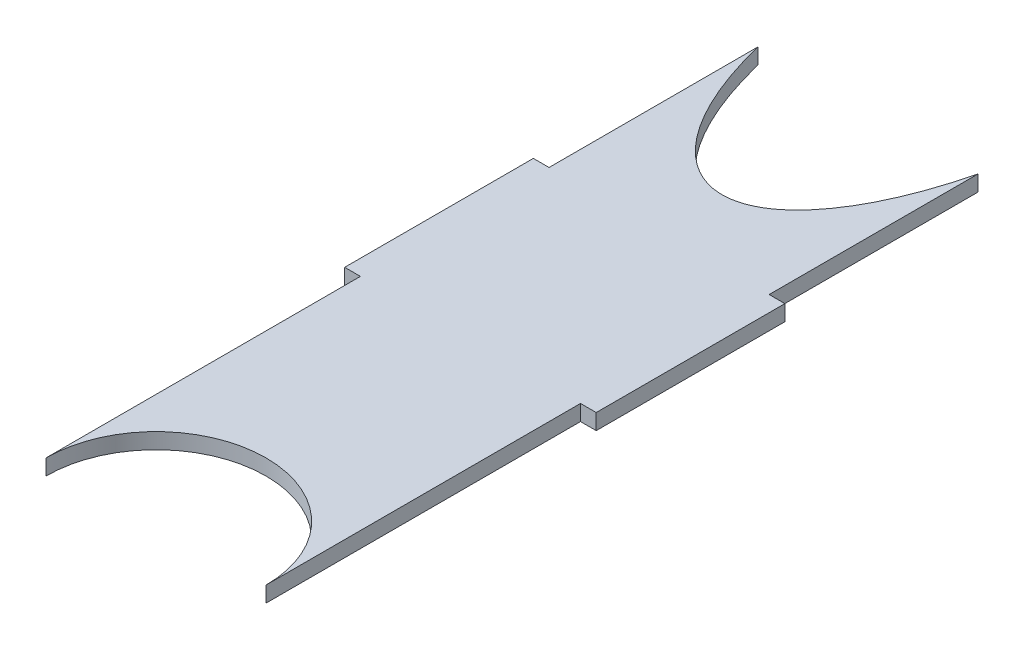
SolidWorks part; units mm, degrees
material "AISI 4130 Steel, annealed at 865C"
ref_plane "X-Y Datum" through (0, 0, 0) normal (0, 0, 1) x (1, 0, 0)
ref_plane "X-Z Datum" through (0, 0, 0) normal (0, 1, 0) x (1, 0, 0)
ref_plane "Y-Z Datum" through (0, 0, 0) normal (1, 0, 0) x (0, 0, -1)
sketch "Sketch1" plane through (0, 0, 0) normal (0, 1, 0) x (1, 0, 0)
  line L1 (11.1125, 42.8625) -> (-11.1125, 42.8625) construction
  line L2 (11.1125, 42.8625) -> (11.1125, -42.8625)
  line L3 (11.1125, -42.8625) -> (-11.1125, -42.8625) construction
  line L4 (-11.1125, 42.8625) -> (-11.1125, -42.8625)
  line L5 (11.1125, 42.8625) -> (-11.1125, -42.8625) construction
  line L6 (11.1125, -42.8625) -> (-11.1125, 42.8625) construction
  line L7 (11.1125, -11.1125) -> (12.7, -11.1125)
  line L8 (11.1125, -11.1125) -> (11.1125, 7.9375)
  line L9 (11.1125, 7.9375) -> (12.7, 7.9375)
  line L10 (12.7, -11.1125) -> (12.7, 7.9375)
  line L11 (-11.1125, -11.1125) -> (-12.7, -11.1125)
  line L12 (-11.1125, -11.1125) -> (-11.1125, 7.9375)
  line L13 (-11.1125, 7.9375) -> (-12.7, 7.9375)
  line L14 (-12.7, -11.1125) -> (-12.7, 7.9375)
  arc A0 (11.1125, -42.8625) -> (-11.1125, -42.8625) centre (0, -42.8625) ccw
  ellipse E0 centre (0, 42.8625) end of major axis (0, 71.4375) minor radius 12.7 (-11.1125, 29.0287) -> (11.1125, 29.0287) ccw
  point P0 (0, 0)
  dimension "D5" = 6.35
  dimension "D1" = 1.5875
  dimension "D2" = 25.4
  dimension "D3" = 19.05
  dimension "D6" = 57.15
  dimension "1.125" = 28.575
extrude "Boss-Extrude1" add sketch "Sketch1" along normal blind 1.5875
